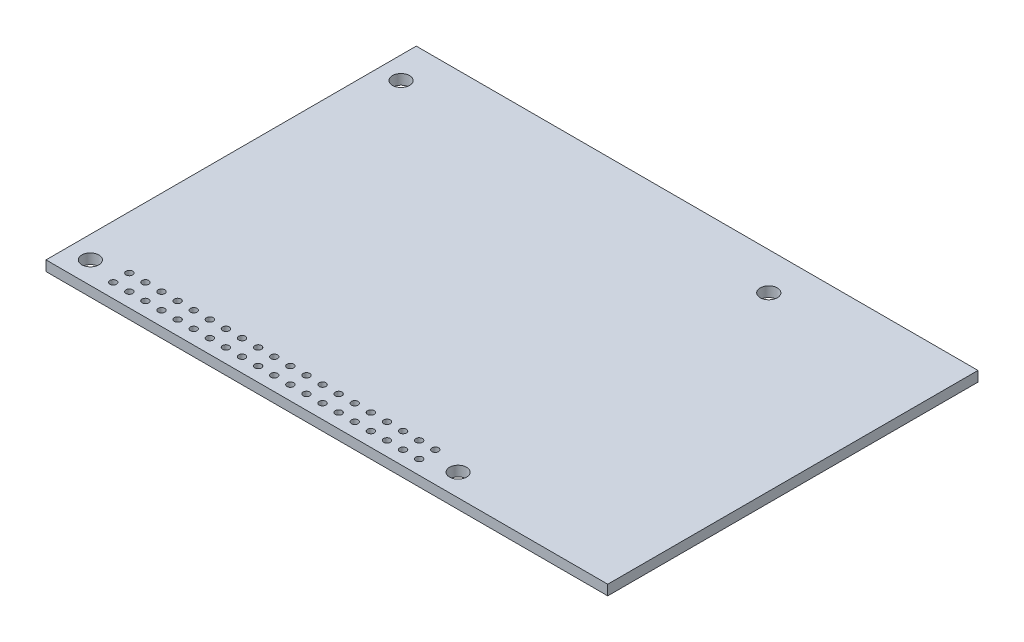
SolidWorks part; units mm, degrees
ref_plane "Front Plane" through (0, 0, 0) normal (0, 0, 1) x (1, 0, 0)
ref_plane "Top Plane" through (0, 0, 0) normal (0, 1, 0) x (1, 0, 0)
ref_plane "Right Plane" through (0, 0, 0) normal (1, 0, 0) x (0, 0, -1)
sketch "Sketch1" plane through (0, 0, 0) normal (0, 1, 0) x (1, 0, 0)
  line L5 (-32.5, -3.5) -> (56.1, -3.5)
  line L6 (-32.5, -3.5) -> (-32.5, 54.9)
  line L7 (-32.5, 54.9) -> (56.1, 54.9)
  line L8 (56.1, -3.5) -> (56.1, 54.9)
  dimension "D1" = 32.5
  dimension "D2" = 56.1
  dimension "D3" = 54.9
  dimension "D4" = 3.5
extrude "Boss-Extrude1" add sketch "Sketch1" along normal blind 1.6
hole_wizard "Ø2.7 (2.7) Diameter Hole1" positions "3DSketch1" profile "Sketch2" hole size "Ø2.7" standard "ISO"
sketch3d "3DSketch1"
  point P0 (-29, 1.6, -49)
  point P2 (29, 1.6, -49)
  point P4 (29, 1.6, 0)
  point P6 (-29, 1.6, 0)
  point P9 (0, 0, 0)
  point P10 (0, 0, 0)
  point P11 (0, 0, 0)
  point P12 (0, 0, 0)
  point P13 (0, 0, 0)
  point P14 (0, 0, 0)
  dimension "D1" = 29
  dimension "D2" = 29
  dimension "D3" = 49
sketch "Sketch2" plane through (-29, 1.6, -49) normal (1, 0, 0) x (0, 0, 1)
  line L0 (0, 0) -> (0, 5.9112)
  line L1 (0, 5.9112) -> (1.35, 5.1)
  line L2 (1.35, 5.1) -> (1.35, 0)
  line L5 (1.35, 0) -> (0, 0)
  line L10 (0, 5.9112) -> (-1.35, 5.1) construction
  line L11 (0, -6.35) -> (0, 107.95) construction
  dimension "Hole Dia." = 2.7
  dimension "Hole Depth" = 5.1
  dimension "Drill Angle" = 118
hole_wizard "Ø1.05 (1.05) Diameter Hole1" positions "3DSketch2" profile "Sketch3" hole size "Ø1.05" standard "ISO"
sketch3d "3DSketch2"
  point P0 (-24.13, 1.6, 1.27)
  dimension "D1" = 1.27
  dimension "D2" = 24.13
sketch "Sketch3" plane through (-24.13, 1.6, 1.27) normal (1, 0, 0) x (0, 0, 1)
  line L0 (0, 0) -> (0, 5.4155)
  line L1 (0, 5.4155) -> (0.525, 5.1)
  line L2 (0.525, 5.1) -> (0.525, 0)
  line L5 (0.525, 0) -> (0, 0)
  line L10 (0, 5.4155) -> (-0.525, 5.1) construction
  line L11 (0, -6.35) -> (0, 107.95) construction
  dimension "Hole Dia." = 1.05
  dimension "Hole Depth" = 5.1
  dimension "Drill Angle" = 118
pattern_linear "LPattern1" count 20 spacing 2.54 along (1, 0, 0) count 2 spacing 2.54 along (0, 0, -1) of "Ø1.05 (1.05) Diameter Hole1"
